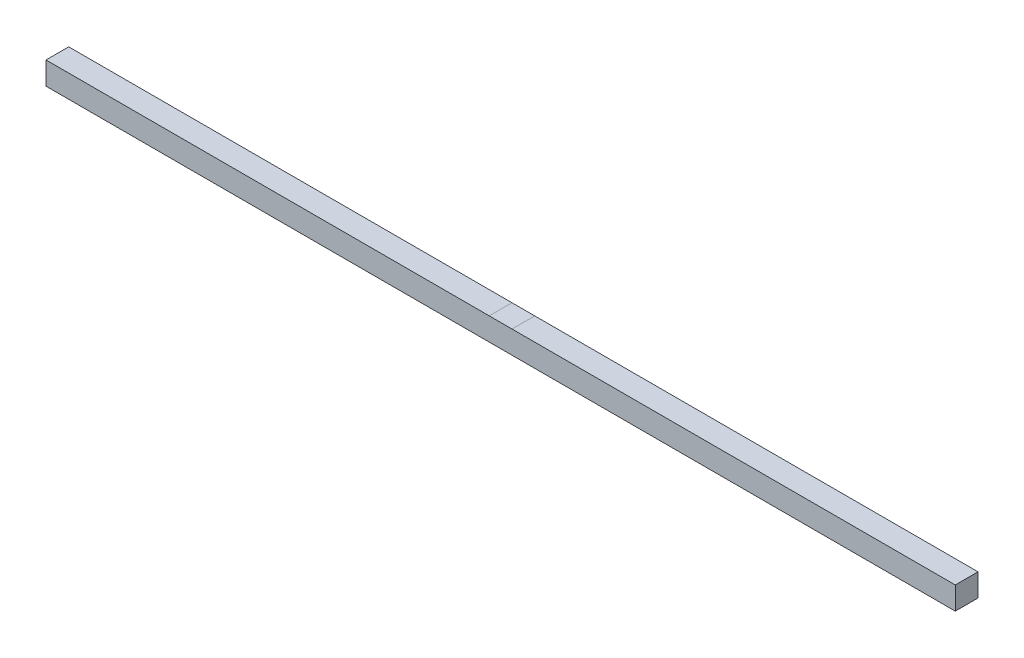
SolidWorks part; units mm, degrees
ref_plane "Front Plane" through (0, 0, 0) normal (0, 0, 1) x (1, 0, 0)
ref_plane "Top Plane" through (0, 0, 0) normal (0, 1, 0) x (1, 0, 0)
ref_plane "Right Plane" through (0, 0, 0) normal (1, 0, 0) x (0, 0, -1)
other "Configuration Table"
sketch "Sketch1" plane through (0, 0, 0) normal (0, 0, 1) x (1, 0, 0)
  line L0 (27.94, 0) -> (-27.94, 0) construction
  line L1 (-76.2, 50.8) -> (1955.8, 50.8)
  line L2 (-76.2, 50.8) -> (-76.2, 0)
  line L3 (-76.2, 0) -> (1955.8, 0)
  line L4 (1955.8, 50.8) -> (1955.8, 0)
  dimension "D1" = 50.8
  dimension "D2" = 2032
extrude "Extrude1" add sketch "Sketch1" along normal blind 50.8
sketch "Sketch2" plane through (0, 254, 0) normal (0, 1, 0) x (1, 0, 0)
  line L0 (914.4, -101.6) -> (914.4, 50.8) construction
  line L1 (914.4, 25.4) -> (965.2, 25.4)
  line L2 (914.4, 25.4) -> (914.4, -76.2)
  line L3 (914.4, -76.2) -> (965.2, -76.2)
  line L4 (965.2, 25.4) -> (965.2, -76.2)
split line "Split Line1"
